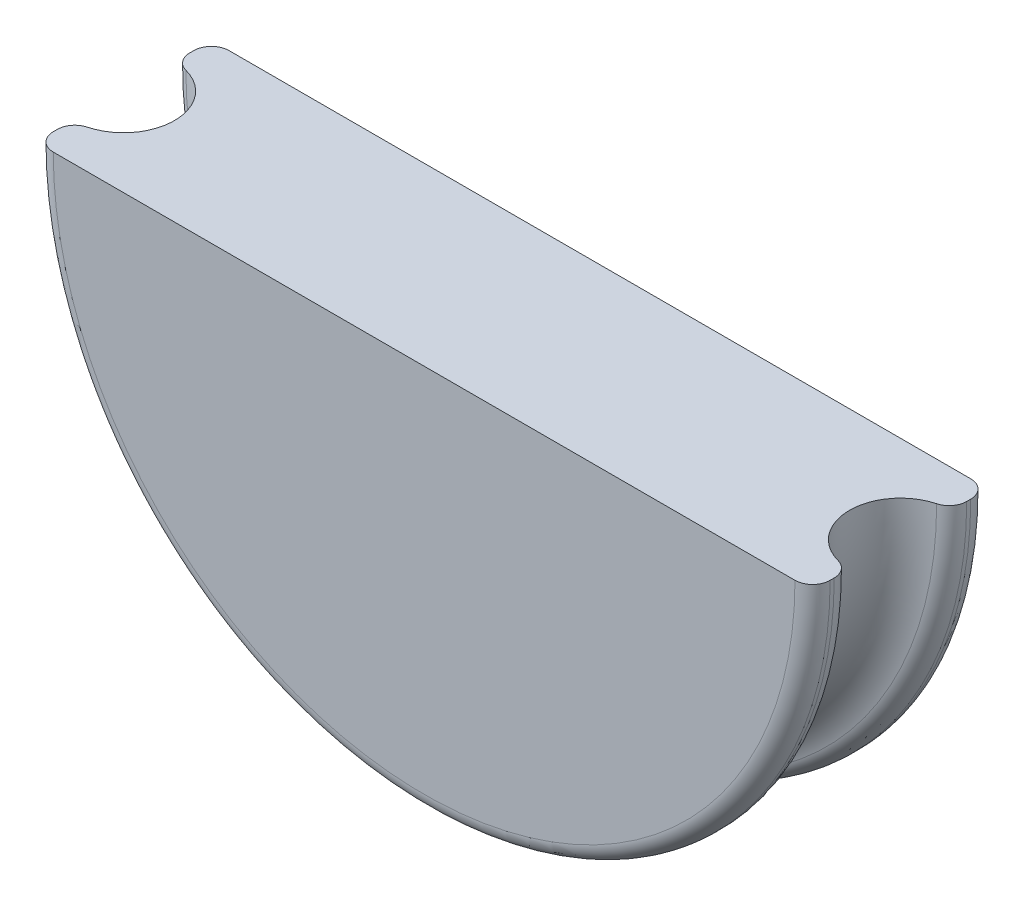
SolidWorks part; units mm, degrees
ref_plane "Front Plane" through (0, 0, 0) normal (0, 0, 1) x (1, 0, 0)
ref_plane "Top Plane" through (0, 0, 0) normal (0, 1, 0) x (1, 0, 0)
ref_plane "Right Plane" through (0, 0, 0) normal (1, 0, 0) x (0, 0, -1)
sketch "Sketch1" plane through (0, 0, 0) normal (0, 1, 0) x (1, 0, 0)
  line L0 (0, -6.35) -> (0, 6.35)
  line L1 (0, 0) -> (28.067, 0) construction
  line L2 (0, 6.35) -> (26.797, 6.35)
  line L3 (28.067, 5.08) -> (28.067, 4.7874)
  line L4 (28.067, -5.08) -> (28.067, -4.7874)
  line L5 (0, -6.35) -> (26.797, -6.35)
  arc A0 (27.1226, 3.5599) -> (27.1226, -3.5599) centre (28.067, 0) ccw
  arc A1 (28.067, -5.08) -> (26.797, -6.35) centre (26.797, -5.08) cw
  arc A2 (26.797, 6.35) -> (28.067, 5.08) centre (26.797, 5.08) cw
  arc A3 (28.067, -4.7874) -> (27.1226, -3.5599) centre (26.797, -4.7874) ccw
  arc A4 (28.067, 4.7874) -> (27.1226, 3.5599) centre (26.797, 4.7874) cw
  point P4 (0, 0)
  point P11 (24.384, 0)
  point P14 (28.067, -6.35)
  point P17 (28.067, 6.35)
  point P20 (28.067, -3.683)
  point P23 (28.067, 3.683)
  dimension "D2" = 3.683
  dimension "D4" = 1.27
  dimension "D1" = 24.384
  dimension "D3" = 12.7
revolve "Revolve1" add sketch "Sketch1" angle 180 about L0
